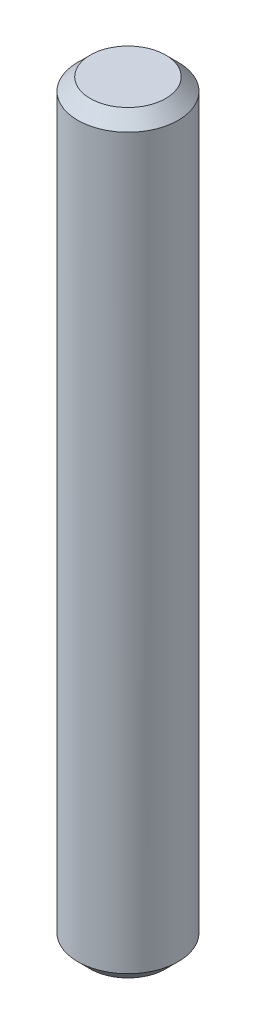
SolidWorks part; units mm, degrees
ref_plane "Front Plane" through (0, 0, 0) normal (0, 0, 1) x (1, 0, 0)
ref_plane "Top Plane" through (0, 0, 0) normal (0, 1, 0) x (1, 0, 0)
ref_plane "Right Plane" through (0, 0, 0) normal (1, 0, 0) x (0, 0, -1)
sketch "Sketch1" plane through (0, 0, 0) normal (0, 0, 1) x (1, 0, 0)
  line L1 (0, 15) -> (2, 15)
  line L2 (0, 15) -> (0, -15)
  line L3 (0, -15) -> (2, -15)
  line L4 (2, 15) -> (2, -15)
  point P4 (0, 0)
  dimension "D1" = 30
  dimension "D2" = 2
revolve "Revolve1" add sketch "Sketch1" angle 360 about L2
chamfer "Chamfer1" distance 0.5 angle 45 2 edges at (-2, -15, 0) (-2, 15, 0)
